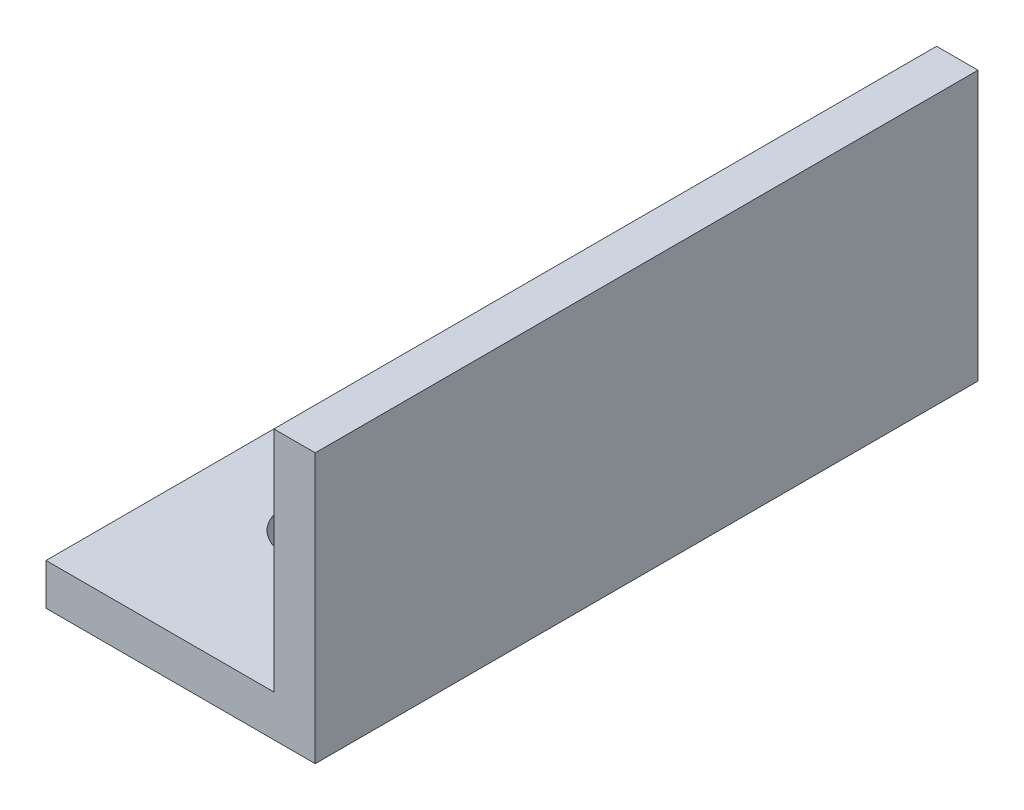
SolidWorks part; units mm, degrees
material "Plain Carbon Steel"
ref_plane "Front Plane" through (0, 0, 0) normal (0, 0, 1) x (1, 0, 0)
ref_plane "Top Plane" through (0, 0, 0) normal (0, 1, 0) x (1, 0, 0)
ref_plane "Right Plane" through (0, 0, 0) normal (1, 0, 0) x (0, 0, -1)
sketch "Sketch1" plane through (0, 0, 0) normal (0, 1, 0) x (1, 0, 0)
  line L1 (0, 0) -> (11, 0)
  line L2 (0, 0) -> (0, 32)
  line L3 (0, 32) -> (11, 32)
  line L4 (11, 0) -> (11, 32)
extrude "Boss-Extrude1" add sketch "Sketch1" along normal blind 2
sketch "Sketch2" plane through (0, 0, 0) normal (0, -1, 0) x (1, 0, 0)
  line L1 (11, 0) -> (13, 0)
  line L2 (11, 0) -> (11, -32)
  line L3 (11, -32) -> (13, -32)
  line L4 (0, 0) -> (0, -32)
  line L5 (0, -32) -> (11, -32)
  line L6 (11, -32) -> (11, 0)
  line L7 (11, 0) -> (0, 0)
  line L8 (0, 0) -> (0, -32)
  line L9 (0, -32) -> (11, -32)
  line L10 (11, -32) -> (11, 0)
  line L11 (11, 0) -> (0, 0)
  line L12 (13, 0) -> (13, -32)
  dimension "D1" = 0
sketch "Sketch3" plane through (0, 2, 0) normal (0, 1, 0) x (1, 0, 0)
  line L1 (11, 0) -> (13, 0)
  line L2 (11, 0) -> (11, 32)
  line L3 (11, 32) -> (13, 32)
  line L4 (0, 32) -> (0, 0)
  line L5 (0, 0) -> (11, 0)
  line L6 (11, 0) -> (11, 32)
  line L7 (11, 32) -> (0, 32)
  line L8 (0, 32) -> (0, 0)
  line L9 (0, 0) -> (11, 0)
  line L10 (11, 0) -> (11, 32)
  line L11 (11, 32) -> (0, 32)
  line L12 (13, 0) -> (13, 32)
  dimension "D1" = 0
sketch "Sketch4" plane through (11, 0, 0) normal (1, 0, 0) x (0, 0, -1)
  line L4 (0, 0) -> (32, 0)
  line L5 (32, 0) -> (32, 2)
  line L6 (32, 2) -> (0, 2)
  line L7 (0, 2) -> (0, 0)
  line L8 (0, 0) -> (32, 0)
  line L9 (32, 0) -> (32, 2)
  line L10 (32, 2) -> (0, 2)
  line L11 (0, 2) -> (0, 0)
  dimension "D1" = 0
extrude "Boss-Extrude2" add sketch "Sketch4" along normal blind 2
sketch "Sketch5" plane through (0, 2, 0) normal (0, 1, 0) x (1, 0, 0)
  line L1 (13, 0) -> (11, 0)
  line L2 (13, 0) -> (13, 32)
  line L3 (13, 32) -> (11, 32)
  line L4 (11, 0) -> (11, 32)
extrude "Boss-Extrude3" add sketch "Sketch5" along normal blind 11
sketch "Sketch6" plane through (0, 2, 0) normal (0, 1, 0) x (1, 0, 0)
  line L0 (0, 16) -> (5.5, 16)
  line L1 (5.5, 16) -> (5.5, 0)
  line L2 (5.5, 16) -> (5.5, 32)
  line L4 (11, 0) -> (11, 32)
  line L5 (11, 32) -> (0, 32)
  line L6 (0, 32) -> (0, 0)
  line L7 (0, 0) -> (11, 0)
  line L8 (11, 0) -> (11, 32)
  line L9 (11, 32) -> (0, 32)
  line L10 (0, 32) -> (0, 0)
  line L11 (0, 0) -> (11, 0)
  circle A0 centre (5.5, 8) radius 2
  circle A1 centre (5.5, 24) radius 2
  dimension "D1" = 0
extrude "Cut-Extrude6" cut sketch "Sketch6" against normal through all contours L1 A0 | L1 A0 | L2 A1 | L2 A1
